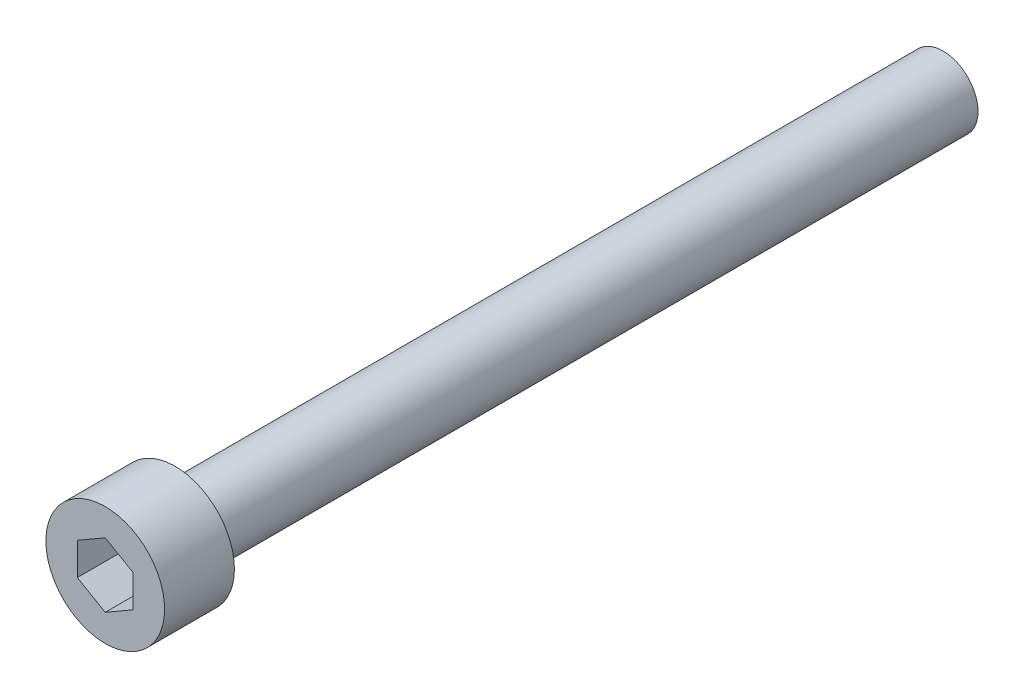
SolidWorks part; units mm, degrees
material "炭素鋼(普通)"
ref_plane "正面" through (0, 0, 0) normal (0, 0, 1) x (1, 0, 0)
ref_plane "平面" through (0, 0, 0) normal (0, 1, 0) x (1, 0, 0)
ref_plane "右側面" through (0, 0, 0) normal (1, 0, 0) x (0, 0, -1)
sketch "ｽｹｯﾁ1" plane through (0, 0, 0) normal (0, 0, 1) x (1, 0, 0)
  circle A0 centre (0, 0) radius 2.5
  dimension "D1" = 5
extrude "ﾎﾞｽ - 押し出し1" add sketch "ｽｹｯﾁ1" along normal blind 55
sketch "ｽｹｯﾁ2" plane through (0, 0, 55) normal (0, 0, 1) x (1, 0, 0)
  circle A0 centre (0, 0) radius 4.25
  dimension "D1" = 8.5
extrude "ﾎﾞｽ - 押し出し2" add sketch "ｽｹｯﾁ2" along normal blind 5
sketch "ｽｹｯﾁ3" plane through (0, 0, 60) normal (0, 0, 1) x (1, 0, 0)
  line L1 (0, 2.3094) -> (-2, 1.1547)
  line L2 (-2, 1.1547) -> (-2, -1.1547)
  line L3 (-2, -1.1547) -> (0, -2.3094)
  line L4 (0, -2.3094) -> (2, -1.1547)
  line L5 (2, -1.1547) -> (2, 1.1547)
  line L6 (2, 1.1547) -> (0, 2.3094)
  circle A0 centre (0, 0) radius 2 construction
  dimension "D1" = 4
extrude "ｶｯﾄ - 押し出し1" cut sketch "ｽｹｯﾁ3" against normal blind 3
